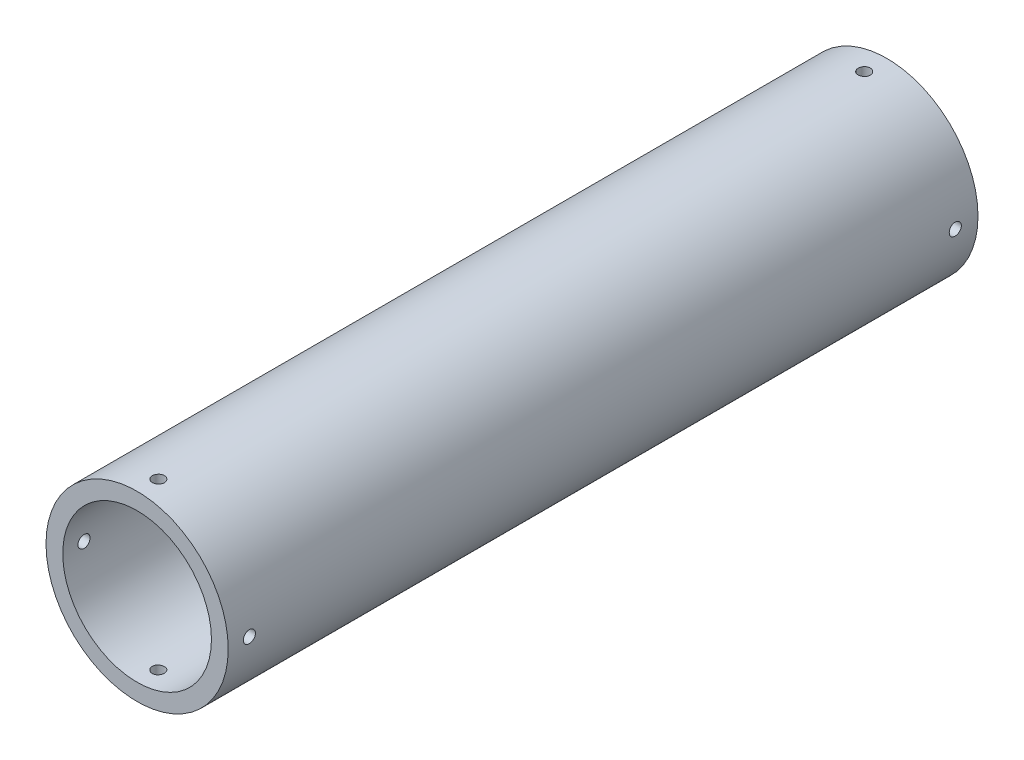
SolidWorks part; units mm, degrees
material "6061 Alloy"
ref_plane "Front Plane" through (0, 0, 0) normal (0, 0, 1) x (1, 0, 0)
ref_plane "Top Plane" through (0, 0, 0) normal (0, 1, 0) x (1, 0, 0)
ref_plane "Right Plane" through (0, 0, 0) normal (1, 0, 0) x (0, 0, -1)
sketch "Sketch1" plane through (0, 0, 0) normal (0, 0, 1) x (1, 0, 0)
  circle A0 centre (0, 0) radius 24.5618
  circle A1 centre (0, 0) radius 30.099
  dimension "D1" = 49.1236
  dimension "D2" = 60.198
extrude "Boss-Extrude1" add sketch "Sketch1" along normal blind 247.7
ref_plane "Plane1" through (0, 0, 7.5) normal (0, 0, -1) x (-1, 0, 0)
hole_wizard "Ø4.0mm Dowel Hole1" positions "3DSketch1" profile "Sketch2" hole size "Ø4.0" standard "ISO"
sketch3d "3DSketch1"
  line L0 (-30.099, 0, 7.5) -> (30.099, 0, 7.5)
  line L2 (0, -30.099, 7.5) -> (0, 30.099, 7.5)
  point P0 (0, 30.099, 7.5)
  point P2 (30.099, 0, 7.5)
  point P4 (0, -30.099, 7.5)
  point P6 (-30.099, 0, 7.5)
  dimension "D1" = 0
sketch "Sketch2" plane through (0, 30.099, 7.5) normal (1, 0, 0) x (0, 0, 1)
  line L0 (0, 0) -> (0, 7.2017)
  line L1 (0, 7.2017) -> (2, 6)
  line L2 (2, 6) -> (2, 0)
  line L5 (2, 0) -> (0, 0)
  line L10 (0, 7.2017) -> (-2, 6) construction
  line L11 (0, -6.35) -> (0, 107.95) construction
  dimension "Hole Dia." = 4
  dimension "Hole Depth" = 6
  dimension "Drill Angle" = 118
ref_plane "Plane2" through (0, 0, 240.7) normal (0, 0, 1) x (1, 0, 0)
hole_wizard "Ø4.0mm Dowel Hole2" positions "3DSketch2" profile "Sketch3" hole size "Ø4.0" standard "ISO"
sketch3d "3DSketch2"
  line L0 (30.099, 0, 240.7) -> (-30.099, 0, 240.7)
  line L2 (0, -30.099, 240.7) -> (0, 30.099, 240.7)
  point P0 (0, -30.099, 240.7)
  point P2 (-30.099, 0, 240.7)
  point P4 (0, 30.099, 240.7)
  point P6 (30.099, 0, 240.7)
  dimension "D1" = 0
sketch "Sketch3" plane through (0, -30.099, 240.7) normal (1, 0, 0) x (0, 0, -1)
  line L0 (0, 0) -> (0, 7.2017)
  line L1 (0, 7.2017) -> (2, 6)
  line L2 (2, 6) -> (2, 0)
  line L5 (2, 0) -> (0, 0)
  line L10 (0, 7.2017) -> (-2, 6) construction
  line L11 (0, -6.35) -> (0, 107.95) construction
  dimension "Hole Dia." = 4
  dimension "Hole Depth" = 6
  dimension "Drill Angle" = 118
